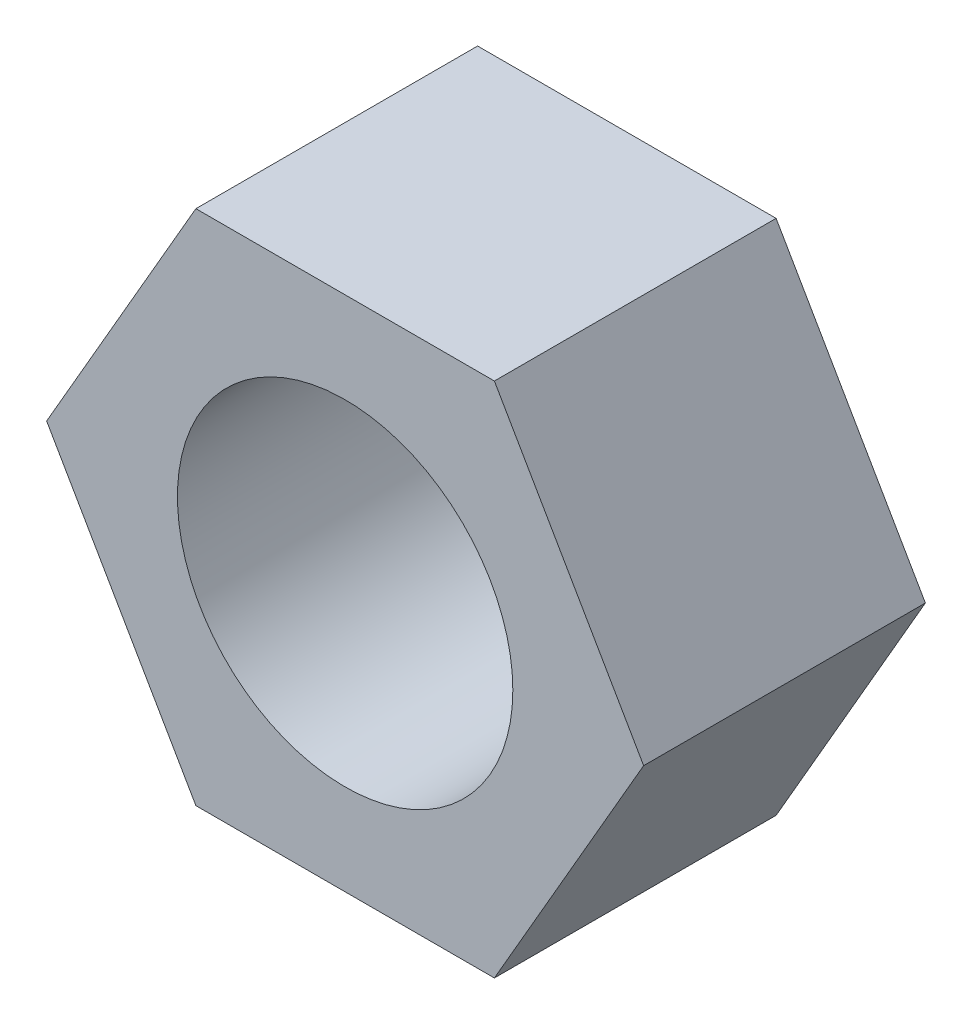
SolidWorks part; units mm, degrees
ref_plane "Płaszczyzna przednia" through (0, 0, 0) normal (0, 0, 1) x (1, 0, 0)
ref_plane "Płaszczyzna górna" through (0, 0, 0) normal (0, 1, 0) x (1, 0, 0)
ref_plane "Płaszczyzna prawa" through (0, 0, 0) normal (1, 0, 0) x (0, 0, -1)
sketch "Sketch1" plane through (0, 0, 0) normal (0, 0, 1) x (1, 0, 0)
  line L1 (8.9, 0) -> (4.45, 7.7076)
  line L2 (4.45, 7.7076) -> (-4.45, 7.7076)
  line L3 (-4.45, 7.7076) -> (-8.9, 0)
  line L4 (-8.9, 0) -> (-4.45, -7.7076)
  line L5 (-4.45, -7.7076) -> (4.45, -7.7076)
  line L6 (4.45, -7.7076) -> (8.9, 0)
  circle A0 centre (0, 0) radius 7.7076 construction
  dimension "e" = 17.8
extrude "Boss-Extrude1" add sketch "Sketch1" along normal blind 8.4
sketch "Sketch2" plane through (0, 0, 8.4) normal (0, 0, 1) x (1, 0, 0)
  circle A0 centre (0, 0) radius 5
  dimension "d" = 10
extrude "Cut-Extrude1" cut sketch "Sketch2" against normal blind 65
